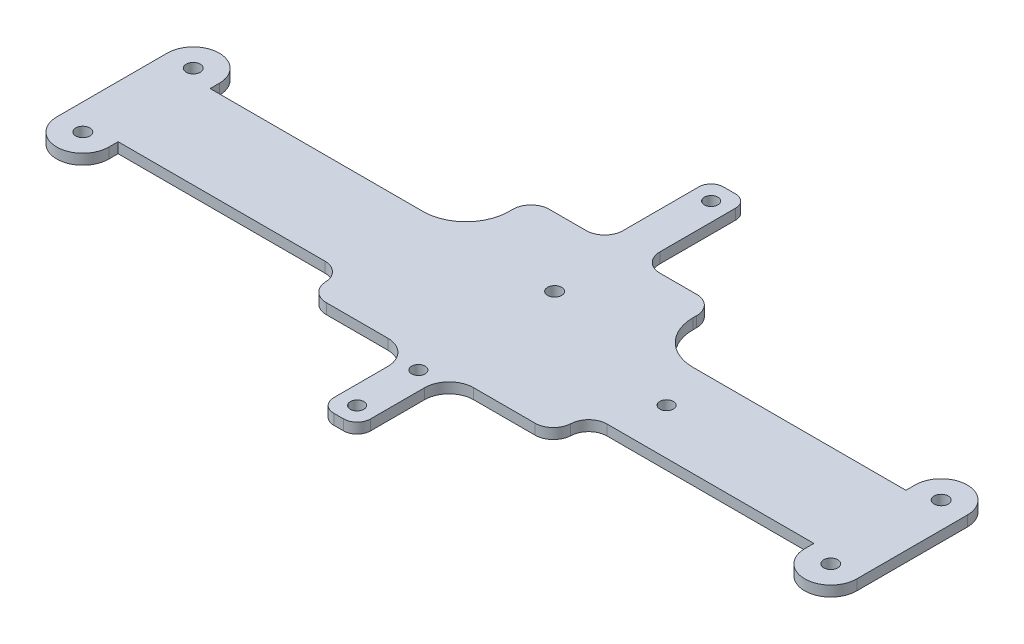
SolidWorks part; units mm, degrees
ref_plane "Płaszczyzna przednia" through (0, 0, 0) normal (0, 0, 1) x (1, 0, 0)
ref_plane "Płaszczyzna górna" through (0, 0, 0) normal (0, 1, 0) x (1, 0, 0)
ref_plane "Płaszczyzna prawa" through (0, 0, 0) normal (1, 0, 0) x (0, 0, -1)
sketch "Szkic1" plane through (0, 7.0875, 0) normal (0, -1, 0) x (1, 0, 0)
  line L0 (-166.869, 45.27) -> (-166.869, 48.27) construction
  line L1 (-166.869, 45.27) -> (-166.869, 48.27)
  line L2 (-44.969, 30.27) -> (-44.969, 31.77) construction
  line L3 (-36.469, 33.27) -> (-36.469, 30.27) construction
  line L4 (-36.469, 48.27) -> (-36.469, 45.27) construction
  line L5 (-44.969, 46.77) -> (-44.969, 48.27) construction
  line L6 (-158.369, 31.77) -> (-158.369, 30.27) construction
  line L7 (-166.869, 30.27) -> (-166.869, 33.27) construction
  line L8 (-158.369, 48.27) -> (-158.369, 46.77) construction
  line L9 (-44.969, 30.27) -> (-44.969, 31.77)
  line L10 (-36.469, 33.27) -> (-36.469, 30.27)
  line L11 (-36.469, 48.27) -> (-36.469, 45.27)
  line L12 (-44.969, 46.77) -> (-44.969, 48.27)
  line L13 (-158.369, 31.77) -> (-158.369, 30.27)
  line L14 (-166.869, 30.27) -> (-166.869, 33.27)
  line L15 (-158.369, 48.27) -> (-158.369, 46.77)
  line L16 (-166.869, 33.27) -> (-166.869, 45.27)
  line L17 (-36.469, 45.27) -> (-36.469, 33.27)
  line L18 (-158.369, 46.77) -> (-124.669, 46.77)
  line L19 (-44.969, 31.77) -> (-79.669, 31.77)
  line L20 (-101.669, 68.1389) -> (-101.669, 67.52) construction
  line L21 (-116.669, 24.77) -> (-116.669, 24.17)
  line L22 (-113.669, 21.17) -> (-107.669, 21.17)
  line L23 (-86.669, 24.17) -> (-86.669, 24.77)
  line L24 (-123.669, 31.77) -> (-158.369, 31.77)
  line L26 (-104.669, 18.17) -> (-104.669, 5.82)
  line L28 (-102.669, 3.82) -> (-100.669, 3.82)
  line L29 (-98.669, 5.82) -> (-98.669, 18.17)
  line L30 (-95.669, 21.17) -> (-89.669, 21.17)
  line L31 (-104.669, 56.52) -> (-104.669, 65.32)
  line L32 (-102.469, 67.52) -> (-100.869, 67.52)
  line L33 (-98.669, 65.32) -> (-98.669, 56.52)
  line L34 (-94.669, 52.52) -> (-84.669, 52.52)
  line L35 (-101.669, 32.32) -> (-101.669, -15.6805) construction
  line L49 (-121.669, 49.77) -> (-121.669, 49.52)
  line L50 (-118.669, 52.52) -> (-108.669, 52.52)
  line L51 (-81.669, 49.52) -> (-81.669, 49.77)
  line L52 (-78.669, 46.77) -> (-44.969, 46.77)
  arc A0 (-44.969, 30.27) -> (-36.469, 30.27) centre (-40.719, 30.27) ccw construction
  arc A1 (-36.469, 48.27) -> (-44.969, 48.27) centre (-40.719, 48.27) ccw construction
  arc A2 (-166.869, 30.27) -> (-158.369, 30.27) centre (-162.619, 30.27) ccw construction
  arc A3 (-158.369, 48.27) -> (-166.869, 48.27) centre (-162.619, 48.27) ccw construction
  arc A4 (-44.969, 30.27) -> (-36.469, 30.27) centre (-40.719, 30.27) ccw
  arc A5 (-36.469, 48.27) -> (-44.969, 48.27) centre (-40.719, 48.27) ccw
  arc A6 (-166.869, 30.27) -> (-158.369, 30.27) centre (-162.619, 30.27) ccw
  arc A7 (-158.369, 48.27) -> (-166.869, 48.27) centre (-162.619, 48.27) ccw
  arc A8 (-86.669, 24.17) -> (-89.669, 21.17) centre (-89.669, 24.17) cw
  arc A9 (-116.669, 24.17) -> (-113.669, 21.17) centre (-113.669, 24.17) ccw
  arc A10 (-79.669, 31.77) -> (-86.669, 24.77) centre (-79.669, 24.77) ccw
  arc A11 (-123.669, 31.77) -> (-116.669, 24.77) centre (-123.669, 24.77) cw
  arc A16 (-163.769, 30.27) -> (-161.469, 30.27) centre (-162.619, 30.27) ccw construction
  arc A17 (-161.469, 48.27) -> (-163.769, 48.27) centre (-162.619, 48.27) ccw construction
  arc A18 (-39.569, 48.27) -> (-41.869, 48.27) centre (-40.719, 48.27) ccw construction
  arc A19 (-41.869, 30.27) -> (-39.569, 30.27) centre (-40.719, 30.27) ccw construction
  circle A24 centre (-162.619, 30.27) radius 1.15
  circle A25 centre (-162.619, 48.27) radius 1.15
  circle A26 centre (-40.719, 48.27) radius 1.15
  circle A27 centre (-40.719, 30.27) radius 1.15
  arc A28 (-81.669, 49.77) -> (-78.669, 46.77) centre (-78.669, 49.77) ccw
  arc A29 (-84.669, 52.52) -> (-81.669, 49.52) centre (-84.669, 49.52) cw
  arc A30 (-121.669, 49.52) -> (-118.669, 52.52) centre (-118.669, 49.52) cw
  arc A31 (-121.669, 49.77) -> (-124.669, 46.77) centre (-124.669, 49.77) cw
  circle A33 centre (-101.669, 6.82) radius 1.1
  arc A34 (-104.669, 5.82) -> (-102.669, 3.82) centre (-102.669, 5.82) ccw
  arc A35 (-100.669, 3.82) -> (-98.669, 5.82) centre (-100.669, 5.82) ccw
  arc A36 (-98.669, 18.17) -> (-95.669, 21.17) centre (-95.669, 18.17) cw
  arc A37 (-104.669, 18.17) -> (-107.669, 21.17) centre (-107.669, 18.17) ccw
  arc A38 (-98.669, 65.32) -> (-100.869, 67.52) centre (-100.869, 65.32) ccw
  arc A39 (-104.669, 65.32) -> (-102.469, 67.52) centre (-102.469, 65.32) cw
  arc A40 (-108.669, 52.52) -> (-104.669, 56.52) centre (-108.669, 56.52) ccw
  arc A41 (-94.669, 52.52) -> (-98.669, 56.52) centre (-94.669, 56.52) cw
  circle A42 centre (-76.469, 39.27) radius 1.1
  circle A43 centre (-101.669, 54.52) radius 1.1
  circle A44 centre (-101.669, 64.52) radius 1.1
  circle A45 centre (-101.669, 32.32) radius 1.15
  point P35 (-116.669, 31.77)
  point P39 (-70.0702, 39.27)
  point P50 (-81.669, 46.77)
  point P60 (-162.619, 52.52)
  point P79 (-98.669, 21.17)
  point P96 (-98.669, 52.52)
  dimension "D4" = 3
  dimension "D5" = 7
  dimension "D6" = 31.35
  dimension "D7" = 20
  dimension "D9" = 3
  dimension "D12" = 25.5
  dimension "D16" = 2.2
  dimension "D17" = 2
  dimension "D19" = 3
  dimension "D20" = 2.2
  dimension "D22" = 4
  dimension "D23" = 2.2
  dimension "D25" = 2.2
  dimension "D26" = 2.2
  dimension "D13" = 2.3
  dimension "D1" = 15
  dimension "D2" = 15
  dimension "D3" = 25.6
  dimension "D8" = 20
  dimension "D10" = 0
  dimension "D11" = 14.35
  dimension "D14" = 3
  dimension "D15" = 3
  dimension "D18" = 3
  dimension "D21" = 15
  dimension "D24" = 40
  dimension "D27" = 7.5
  dimension "D28" = 3
  dimension "D29" = 3
  dimension "D30" = 10
  dimension "D31" = 3
extrude "Dodanie-wyciągnięcie1" add sketch "Szkic1" along normal blind 1.7
